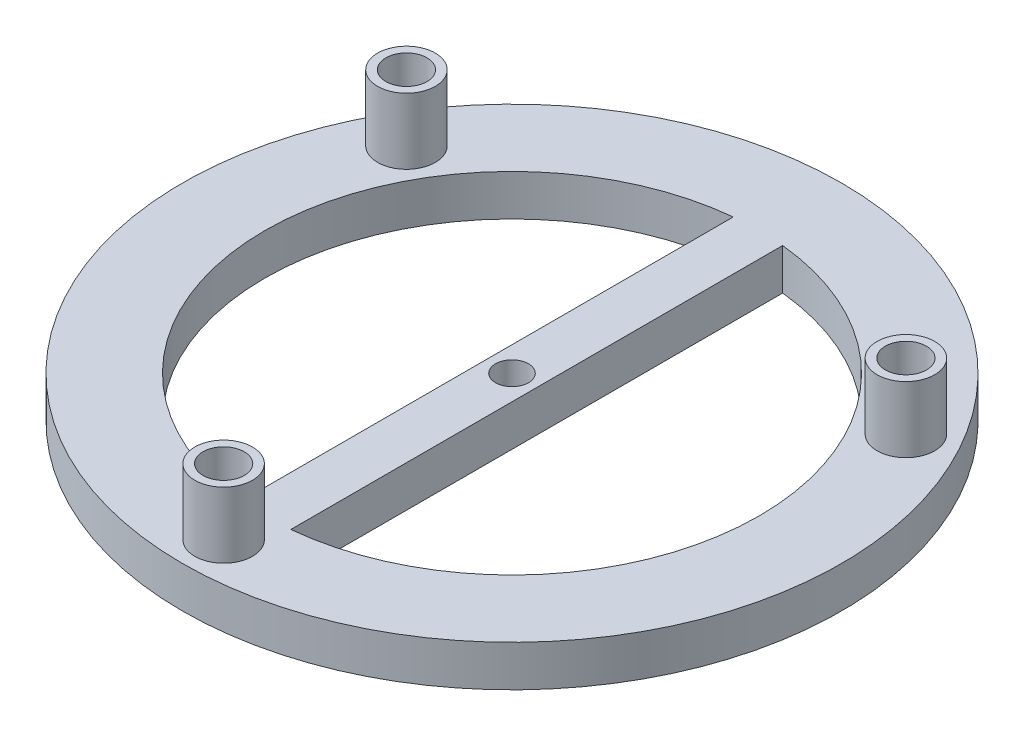
SolidWorks part; units mm, degrees
ref_plane "前视基准面" through (0, 0, 0) normal (0, 0, 1) x (1, 0, 0)
ref_plane "上视基准面" through (0, 0, 0) normal (0, 1, 0) x (1, 0, 0)
ref_plane "右视基准面" through (0, 0, 0) normal (1, 0, 0) x (0, 0, -1)
sketch "草图3" plane through (0, 0, 0) normal (0, 1, 0) x (1, 0, 0)
  circle A0 centre (0, 0) radius 40
  dimension "D1" = 80
extrude "凸台-拉伸2" add sketch "草图3" along normal blind 5
sketch "草图5" plane through (0, 5, 0) normal (0, 1, 0) x (1, 0, 0)
  line L1 (3, 29.8496) -> (3, -29.8496)
  line L2 (-3, 29.8496) -> (-3, -29.8496)
  circle A0 centre (0, 0) radius 30
  dimension "D1" = 60
extrude "切除-拉伸2" cut sketch "草图5" against normal blind 10 contours L2 A0 | L1 A0
sketch "草图6" plane through (0, 5, 0) normal (0, 1, 0) x (1, 0, 0)
  circle A0 centre (0, 0) radius 2
  dimension "D1" = 4
extrude "切除-拉伸3" cut sketch "草图6" against normal blind 10
sketch "草图8" plane through (0, 5, 0) normal (0, 1, 0) x (1, 0, 0)
  circle A0 centre (0, 0) radius 35 construction
  circle A1 centre (0, -35) radius 3.5
  circle A2 centre (0, -35) radius 2.5
  dimension "D1" = 70
  dimension "D2" = 7
  dimension "D3" = 5
extrude "凸台-拉伸3" add sketch "草图8" along normal blind 8
pattern_circular "阵列(圆周)1" count 3 over 360 about axis through (0, 0, 0) along (0, 1, 0) of "凸台-拉伸3"
